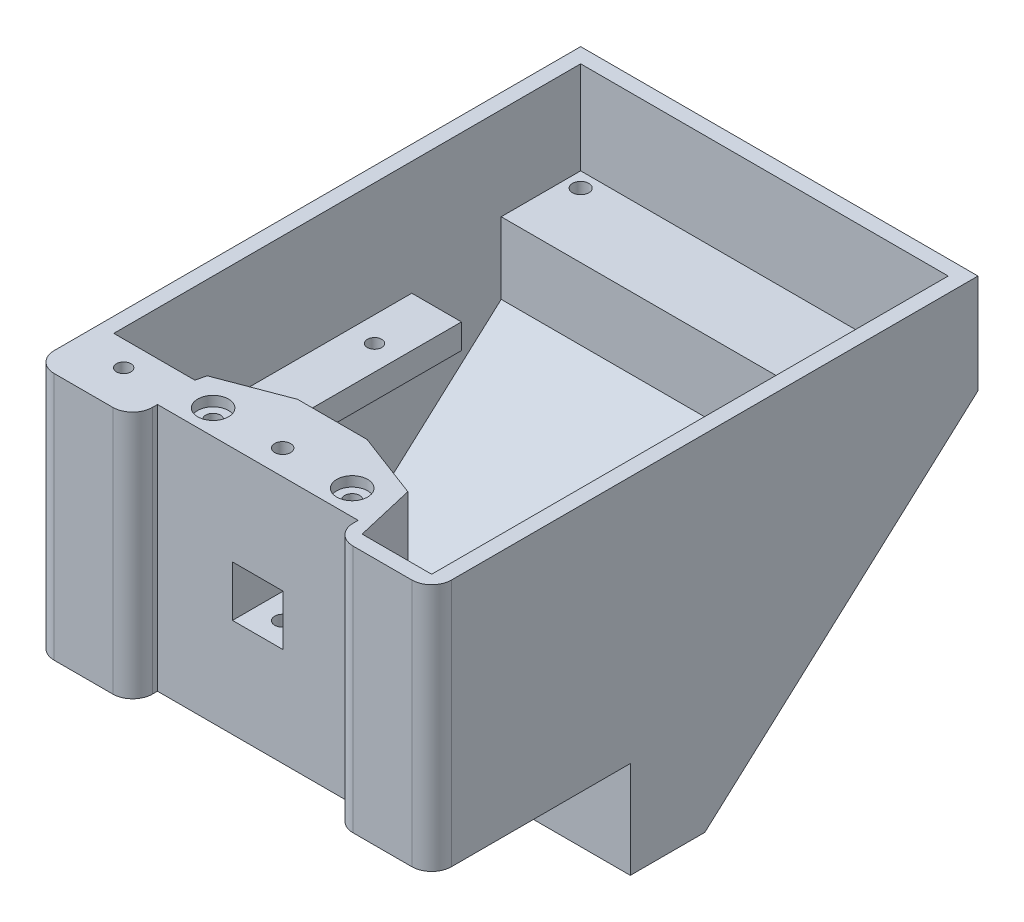
SolidWorks part; units mm, degrees
ref_plane "Спереди" through (0, 0, 0) normal (0, 0, 1) x (1, 0, 0)
ref_plane "Сверху" through (0, 0, 0) normal (0, 1, 0) x (1, 0, 0)
ref_plane "Справа" through (0, 0, 0) normal (1, 0, 0) x (0, 0, -1)
sketch "Sketch2" plane through (0, 0, 0) normal (1, 0, 0) x (0, 0, -1)
  line L0 (-27.3205, 20.9982) -> (-27.3205, -29.0018)
  line L1 (-27.3205, -29.0018) -> (12.6795, -29.0018)
  line L2 (12.6795, -29.0018) -> (12.6795, -48.5114)
  line L3 (12.6795, -48.5114) -> (27.6795, -48.5114)
  line L4 (82.6795, 20.9982) -> (82.6795, 0.9982)
  line L5 (82.6795, 20.9982) -> (-27.3205, 20.9982)
  line L6 (82.6795, 0.9982) -> (27.6795, -48.5114)
  dimension "D1" = 110
  dimension "D2" = 50
  dimension "D3" = 40
  dimension "D4" = 15
  dimension "D5" = 20
extrude "Boss-Extrude1" add sketch "Sketch2" along normal blind 80
shell "Shell1" thickness 3
sketch "Sketch3" plane through (0, 0, 24.3205) normal (0, 0, -1) x (-1, 0, 0)
  line L0 (-40, 20.9982) -> (-40, -26.0018) construction
  line L3 (-77, 20.9982) -> (-3, 20.9982) construction
  line L4 (-77, -26.0018) -> (-3, -26.0018) construction
  line L6 (-17, 20.9982) -> (-63, 20.9982)
  line L7 (-17, 20.9982) -> (-17, -26.0018)
  line L8 (-17, -26.0018) -> (-63, -26.0018)
  line L9 (-63, 20.9982) -> (-63, -26.0018)
  line L10 (-17, 20.9982) -> (-63, -26.0018) construction
  line L11 (-17, -26.0018) -> (-63, 20.9982) construction
  point P6 (-40, -2.5018)
  dimension "D1" = 46
extrude "Boss-Extrude2" add sketch "Sketch3" along normal blind 17
sketch "Sketch4" plane through (0, 0, 27.3205) normal (0, 0, 1) x (1, 0, 0)
  line L0 (0, 20.9982) -> (80, -29.0018) construction
  line L2 (45.1, -9.1018) -> (34.9, -9.1018)
  line L3 (45.1, -9.1018) -> (45.1, 1.0982)
  line L4 (45.1, 1.0982) -> (34.9, 1.0982)
  line L5 (34.9, -9.1018) -> (34.9, 1.0982)
  line L6 (45.1, -9.1018) -> (34.9, 1.0982) construction
  line L7 (45.1, 1.0982) -> (34.9, -9.1018) construction
  point P4 (40, -4.0018)
  dimension "D1" = 10.2
extrude "Cut-Extrude1" cut sketch "Sketch4" against normal up to surface (20 mm away) up to face at (40, -2.5018, 7.3205)
sketch "Sketch6" plane through (0, -29.0018, 0) normal (0, -1, 0) x (1, 0, 0)
  line L0 (40, 27.3205) -> (40, -12.6795) construction
  line L1 (47.5, -5.4795) -> (32.5, -5.4795)
  line L2 (47.5, -5.4795) -> (47.5, 7.3205)
  line L3 (47.5, 7.3205) -> (32.5, 7.3205)
  line L4 (32.5, -5.4795) -> (32.5, 7.3205)
  line L5 (47.5, -5.4795) -> (32.5, 7.3205) construction
  line L6 (47.5, 7.3205) -> (32.5, -5.4795) construction
  line L7 (80, -12.6795) -> (0, -12.6795) construction
  line L9 (80, 27.3205) -> (0, 27.3205) construction
  point P0 (40, 0.9205)
  dimension "D1" = 15
  dimension "D2" = 12.8
  dimension "D4" = 20
extrude "Cut-Extrude2" cut sketch "Sketch6" against normal up to surface (3 mm away) up to face at (40, -26.0018, 10.0705)
sketch "Sketch7" plane through (0, 0, 27.3205) normal (0, 0, 1) x (1, 0, 0)
  line L0 (40, 20.9982) -> (40, -29.0018) construction
  line L1 (80, 20.9982) -> (0, 20.9982) construction
  line L2 (80, -29.0018) -> (0, -29.0018) construction
  line L4 (60.2, -29.0018) -> (19.8, -29.0018)
  line L5 (60.2, -29.0018) -> (60.2, 20.9982)
  line L6 (60.2, 20.9982) -> (19.8, 20.9982)
  line L7 (19.8, -29.0018) -> (19.8, 20.9982)
  line L8 (60.2, -29.0018) -> (19.8, 20.9982) construction
  line L9 (60.2, 20.9982) -> (19.8, -29.0018) construction
  point P6 (40, -4.0018)
  dimension "D1" = 40.4
extrude "Cut-Extrude3" cut sketch "Sketch7" against normal blind 5
fillet "Fillet1" radius 4 4 edges at (19.8, -4.0018, 27.3205) (60.2, -4.0018, 27.3205) (80, -4.0018, 27.3205) (0, -4.0018, 27.3205)
sketch "Sketch12" plane through (0, 20.9982, 0) normal (0, 1, 0) x (1, 0, 0)
  line L0 (19.8, -22.3205) -> (19.8, -12.3205) construction
  line L1 (19.8, -12.3205) -> (60.2, -12.3205) construction
  line L2 (60.2, -12.3205) -> (60.2, -22.3205) construction
  line L3 (33, -7.3205) -> (19.8, -12.3205)
  line L4 (17, -7.3205) -> (63, -7.3205) construction
  line L5 (19.8, -12.3205) -> (17, -24.3205)
  line L6 (17, -24.3205) -> (17, -7.3205)
  line L7 (17, -7.3205) -> (33, -7.3205)
  line L8 (47, -7.3205) -> (63, -7.3205)
  line L9 (63, -7.3205) -> (63, -24.3205)
  line L10 (63, -24.3205) -> (60.2, -12.3205)
  line L11 (60.2, -12.3205) -> (47, -7.3205)
  dimension "D1" = 10
  dimension "D2" = 16
extrude "Cut-Extrude7" cut sketch "Sketch12" against normal up to surface (47 mm away) up to face at (40, -26.0018, 7.0205)
sketch "Sketch13" plane through (0, 20.9982, 0) normal (0, 1, 0) x (1, 0, 0)
  line L0 (19.8, -22.3205) -> (19.8, -12.3205) construction
  line L1 (19.8, -12.3205) -> (60.2, -12.3205) construction
  line L2 (60.2, -12.3205) -> (60.2, -22.3205) construction
  line L3 (60.2, -17.3205) -> (19.8, -17.3205) construction
  circle A0 centre (26, -17.3205) radius 1.5
  circle A1 centre (54, -17.3205) radius 1.5
  point P14 (40, -17.3205)
  dimension "D1" = 3
  dimension "D2" = 28
  dimension "D3" = 14
  dimension "D4" = 6.2
extrude "Cut-Extrude8" cut sketch "Sketch13" against normal blind 25
sketch "Sketch14" plane through (0, 20.9982, 0) normal (0, 1, 0) x (1, 0, 0)
  circle A0 centre (26, -17.3205) radius 3.1
  circle A1 centre (54, -17.3205) radius 3.1
  dimension "D1" = 6.2
extrude "Cut-Extrude9" cut sketch "Sketch14" against normal blind 2
sketch "Sketch17" plane through (77, 0, 0) normal (-1, 0, 0) x (0, 0, 1)
  line L0 (-45.6795, -2.0018) -> (-0.6795, -2.0018)
  line L1 (-0.6795, -2.0018) -> (-0.6795, -7.0018)
  line L2 (-0.6795, -7.0018) -> (-45.6795, -7.0018)
  line L3 (-45.6795, -7.0018) -> (-45.6795, -2.0018)
  line L4 (-79.6795, 20.9982) -> (24.3205, 20.9982) construction
  line L5 (-79.6795, 2.3342) -> (-79.6795, 20.9982) construction
  dimension "D1" = 45
  dimension "D2" = 5
  dimension "D3" = 23
  dimension "D4" = 34
extrude "Boss-Extrude5" add sketch "Sketch17" along normal up to surface (74 mm away) up to face at (3, -14.0994, -24.0865)
sketch "Sketch18" plane through (0, -2.0018, 0) normal (0, 1, 0) x (1, 0, 0)
  line L0 (40, 0.6795) -> (40, 45.6795) construction
  line L1 (3, 0.6795) -> (77, 0.6795) construction
  line L2 (3, 45.6795) -> (77, 45.6795) construction
  line L3 (77, 0.6795) -> (77, 45.6795) construction
  line L4 (13, 0.6795) -> (67, 0.6795)
  line L5 (13, 0.6795) -> (13, 45.6795)
  line L6 (13, 45.6795) -> (67, 45.6795)
  line L7 (67, 0.6795) -> (67, 45.6795)
  line L8 (13, 0.6795) -> (67, 45.6795) construction
  line L9 (13, 45.6795) -> (67, 0.6795) construction
  point P6 (40, 23.1795)
  dimension "D1" = 10
extrude "Cut-Extrude10" cut sketch "Sketch18" against normal up to next
sketch "Sketch19" plane through (0, -2.0018, 0) normal (0, 1, 0) x (1, 0, 0)
  line L0 (72, 45.6795) -> (72, 0.6795) construction
  line L1 (67, 45.6795) -> (77, 45.6795) construction
  line L2 (67, 0.6795) -> (77, 0.6795) construction
  line L3 (8, 45.6795) -> (8, 0.6795) construction
  line L4 (3, 45.6795) -> (13, 45.6795) construction
  line L5 (3, 0.6795) -> (13, 0.6795) construction
  circle A0 centre (72, 37.1795) radius 1.45
  circle A1 centre (72, 6.1795) radius 1.45
  circle A2 centre (8, 33.1795) radius 1.45
  circle A3 centre (8, 6.1795) radius 1.45
  point P20 (72, 23.1795)
  point P21 (8, 23.1795)
  dimension "D1" = 2.9
  dimension "D2" = 14
  dimension "D3" = 17
  dimension "D4" = 17
  dimension "D5" = 10
extrude "Cut-Extrude11" cut sketch "Sketch19" against normal up to next
sketch "Sketch21" plane through (0, -26.0018, 0) normal (0, 1, 0) x (1, 0, 0)
  line L0 (3, -24.3205) -> (3, -14.3205)
  line L1 (3, -24.3205) -> (3, 15.6795) construction
  line L2 (3, -14.3205) -> (19.3333, -14.3205)
  line L3 (19.8, -12.3205) -> (17, -24.3205) construction
  line L4 (19.3333, -14.3205) -> (17, -24.3205)
  line L6 (3, -24.3205) -> (17, -24.3205)
  dimension "D1" = 10
extrude "Boss-Extrude6" add sketch "Sketch21" along normal up to surface (47 mm away) up to face at (54, 20.9982, 20.4205)
sketch "Sketch22" plane through (0, 20.9982, 0) normal (0, 1, 0) x (1, 0, 0)
  line L0 (0, 82.6795) -> (0, -23.3205) construction
  line L1 (15.8, -27.3205) -> (4, -27.3205) construction
  circle A0 centre (10, -19.3205) radius 1.45
  dimension "D1" = 2.9
  dimension "D2" = 10
  dimension "D3" = 8
extrude "Cut-Extrude12" cut sketch "Sketch22" against normal through all
sketch "Sketch26" plane through (3, 0, 0) normal (1, 0, 0) x (0, 0, -1)
  line L0 (79.6795, 2.3342) -> (63.6795, 2.3342)
  line L1 (63.6795, 2.3342) -> (63.6795, -12.0686)
  line L2 (26.5281, -45.5114) -> (79.6795, 2.3342) construction
  line L3 (63.6795, -12.0686) -> (79.6795, 2.3342)
  dimension "D1" = 16
extrude "Boss-Extrude7" add sketch "Sketch26" along normal up to surface (74 mm away) up to face at (77, -14.0994, -24.0865)
sketch "Sketch27" plane through (0, 2.3342, 0) normal (0, 1, 0) x (1, 0, 0)
  line L0 (3, 76.6795) -> (77, 76.6795) construction
  line L1 (3, 79.6795) -> (3, 63.6795) construction
  line L2 (77, 79.6795) -> (77, 63.6795) construction
  line L3 (80, 82.6795) -> (0, 82.6795) construction
  circle A0 centre (6, 76.6795) radius 1.65
  circle A1 centre (74, 76.6795) radius 1.65
  point P10 (40, 76.6795)
  dimension "D1" = 3.3
  dimension "D2" = 68
  dimension "D3" = 34
  dimension "D4" = 6
extrude "Cut-Extrude14" cut sketch "Sketch27" against normal blind 10
sketch "Sketch28" plane through (0, 2.3342, 0) normal (0, 1, 0) x (1, 0, 0)
  line L1 (74, 79.9295) -> (71.1854, 78.3045)
  line L2 (71.1854, 78.3045) -> (71.1854, 75.0545)
  line L3 (71.1854, 75.0545) -> (74, 73.4295)
  line L4 (74, 73.4295) -> (76.8146, 75.0545)
  line L5 (76.8146, 75.0545) -> (76.8146, 78.3045)
  line L6 (76.8146, 78.3045) -> (74, 79.9295)
  line L7 (6, 73.4295) -> (8.8146, 75.0545)
  line L8 (8.8146, 75.0545) -> (8.8146, 78.3045)
  line L9 (8.8146, 78.3045) -> (6, 79.9295)
  line L10 (6, 79.9295) -> (3.1854, 78.3045)
  line L11 (3.1854, 78.3045) -> (3.1854, 75.0545)
  line L12 (3.1854, 75.0545) -> (6, 73.4295)
  circle A0 centre (74, 76.6795) radius 3.25 construction
  circle A1 centre (6, 76.6795) radius 3.25 construction
  dimension "D1" = 6.5
extrude "Cut-Extrude15" cut sketch "Sketch28" against normal blind 32 from offset 3 offset against normal yes
sketch "Sketch29" plane through (0, -29.0018, 0) normal (0, -1, 0) x (1, 0, 0)
  line L0 (0, 23.3205) -> (0, -12.6795) construction
  line L1 (7.1854, 17.6955) -> (10, 16.0705)
  line L2 (10, 16.0705) -> (12.8146, 17.6955)
  line L3 (12.8146, 17.6955) -> (12.8146, 20.9455)
  line L4 (12.8146, 20.9455) -> (10, 22.5705)
  line L5 (10, 22.5705) -> (7.1854, 20.9455)
  line L6 (7.1854, 20.9455) -> (7.1854, 17.6955)
  circle A0 centre (10, 19.3205) radius 3.25 construction
  dimension "D1" = 6.5
extrude "Cut-Extrude16" cut sketch "Sketch29" against normal blind 30
sketch "Sketch30" plane through (0, -26.0018, 0) normal (0, 1, 0) x (1, 0, 0)
  line L0 (77, -24.3205) -> (63, -24.3205)
  line L1 (63, -24.3205) -> (60.2, -12.3205)
  line L2 (63, -24.3205) -> (60.2, -12.3205) construction
  line L3 (60.2, -12.3205) -> (77, -12.3205)
  line L4 (77, -24.3205) -> (77, 15.6795) construction
  line L5 (77, -12.3205) -> (77, -24.3205)
  dimension "D1" = 12
extrude "Boss-Extrude8" add sketch "Sketch30" along normal blind 20
sketch "Sketch31" plane through (0, -6.0018, 0) normal (0, 1, 0) x (1, 0, 0)
  line L0 (76, -27.3205) -> (64.2, -27.3205) construction
  line L1 (80, -23.3205) -> (80, 12.6795) construction
  circle A0 centre (72, -21.3205) radius 1.5
  dimension "D3" = 3
  dimension "D1" = 6
  dimension "D2" = 8
extrude "Cut-Extrude17" cut sketch "Sketch31" against normal through all
sketch "Sketch32" plane through (0, -29.0018, 0) normal (0, -1, 0) x (1, 0, 0)
  line L1 (72, 24.5705) -> (69.1854, 22.9455)
  line L2 (69.1854, 22.9455) -> (69.1854, 19.6955)
  line L3 (69.1854, 19.6955) -> (72, 18.0705)
  line L4 (72, 18.0705) -> (74.8146, 19.6955)
  line L5 (74.8146, 19.6955) -> (74.8146, 22.9455)
  line L6 (74.8146, 22.9455) -> (72, 24.5705)
  circle A0 centre (72, 21.3205) radius 3.25 construction
  dimension "D1" = 6.5
extrude "Cut-Extrude18" cut sketch "Sketch32" against normal blind 15
sketch "Sketch33" plane through (0, -2.0018, 0) normal (0, 1, 0) x (1, 0, 0)
  line L0 (67, 40.6795) -> (77, 40.6795)
  line L1 (67, 0.6795) -> (67, 45.6795) construction
  line L2 (77, 0.6795) -> (77, 45.6795) construction
  line L3 (77, 40.6795) -> (77, 45.6795)
  line L4 (77, 45.6795) -> (67, 45.6795)
  line L5 (67, 45.6795) -> (67, 40.6795)
  dimension "D1" = 5
extrude "Cut-Extrude19" cut sketch "Sketch33" against normal up to next
sketch "Sketch34" plane through (0, 20.9982, 0) normal (0, 1, 0) x (1, 0, 0)
  line L0 (54, -17.3205) -> (26, -17.3205) construction
  circle A0 centre (40, -17.3205) radius 1.6
  dimension "D1" = 3.2
extrude "Cut-Extrude20" cut sketch "Sketch34" against normal through all
sketch "Sketch36" plane through (0, -29.0018, 0) normal (0, -1, 0) x (1, 0, 0)
  line L1 (38.375, 20.1351) -> (36.75, 17.3205)
  line L2 (36.75, 17.3205) -> (38.375, 14.5059)
  line L3 (38.375, 14.5059) -> (41.625, 14.5059)
  line L4 (41.625, 14.5059) -> (43.25, 17.3205)
  line L5 (43.25, 17.3205) -> (41.625, 20.1351)
  line L6 (41.625, 20.1351) -> (38.375, 20.1351)
  circle A0 centre (40, 17.3205) radius 3.25 construction
  dimension "D1" = 6.5
extrude "Cut-Extrude22" cut sketch "Sketch36" against normal blind 14
